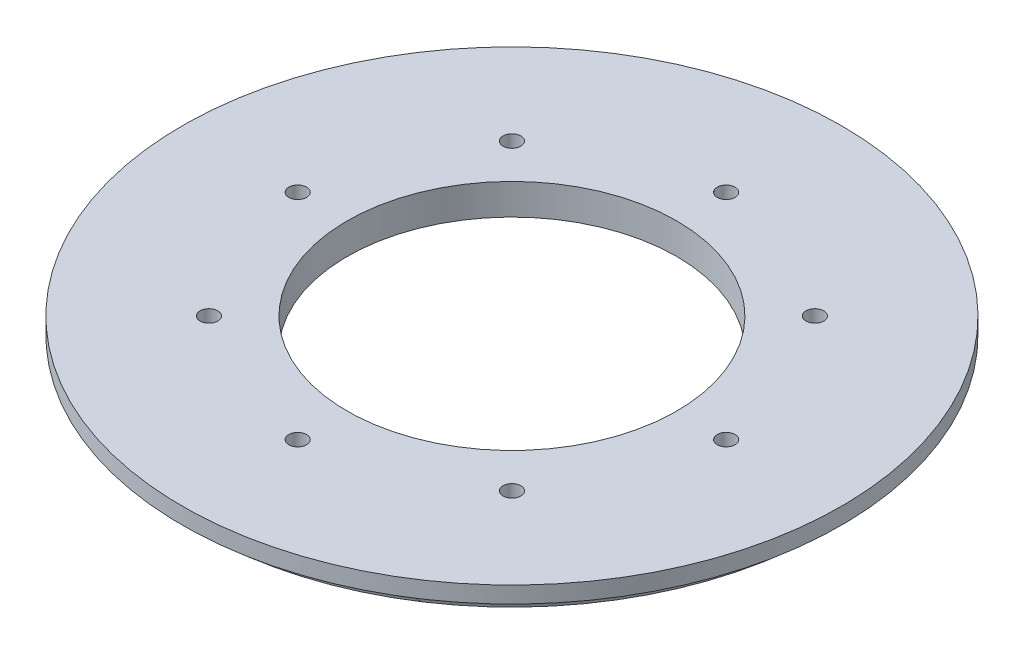
SolidWorks part; units mm, degrees
ref_plane "Front Plane" through (0, 0, 0) normal (0, 0, 1) x (1, 0, 0)
ref_plane "Top Plane" through (0, 0, 0) normal (0, 1, 0) x (1, 0, 0)
ref_plane "Right Plane" through (0, 0, 0) normal (1, 0, 0) x (0, 0, -1)
sketch "Sketch1" plane through (0, 0, 0) normal (0, 0, 1) x (1, 0, 0)
  line L2 (0, 0.315) -> (-47.4844, 0.315)
  line L3 (0, 0.315) -> (0, 4.9999)
  line L4 (0, 4.9999) -> (-50, 4.9999)
  line L5 (-50, 2.4998) -> (-50, 4.9999)
  arc A0 (-47.4844, 0.315) -> (-50, 2.4998) centre (-49.9645, 0.0001) ccw
  dimension "D1" = 5
  dimension "D3" = 50
  dimension "D2" = 5
revolve "Revolve1" add sketch "Sketch1" angle 360 about L3
sketch "Sketch2" plane through (0, 4.9999, 0) normal (0, 1, 0) x (1, 0, 0)
  circle A0 centre (0, 0) radius 32.5 construction
  circle A1 centre (0, 32.5) radius 1.35
  circle A2 centre (22.981, 22.981) radius 1.35
  circle A3 centre (32.5, 0) radius 1.35
  circle A4 centre (22.981, -22.981) radius 1.35
  circle A5 centre (0, -32.5) radius 1.35
  circle A6 centre (-22.981, -22.981) radius 1.35
  circle A7 centre (-32.5, 0) radius 1.35
  circle A8 centre (-22.981, 22.981) radius 1.35
  point P21 (0, 0)
  dimension "D1" = 65
  dimension "D2" = 2.7
  dimension "D3" = 8
extrude "Cut-Extrude1" cut sketch "Sketch2" against normal through all
sketch "Sketch4" plane through (0, 0.315, 0) normal (0, -1, 0) x (1, 0, 0)
  circle A0 centre (0, 0) radius 25 construction
  circle A1 centre (0, 0) radius 25
extrude "Cut-Extrude2" cut sketch "Sketch4" against normal through all
